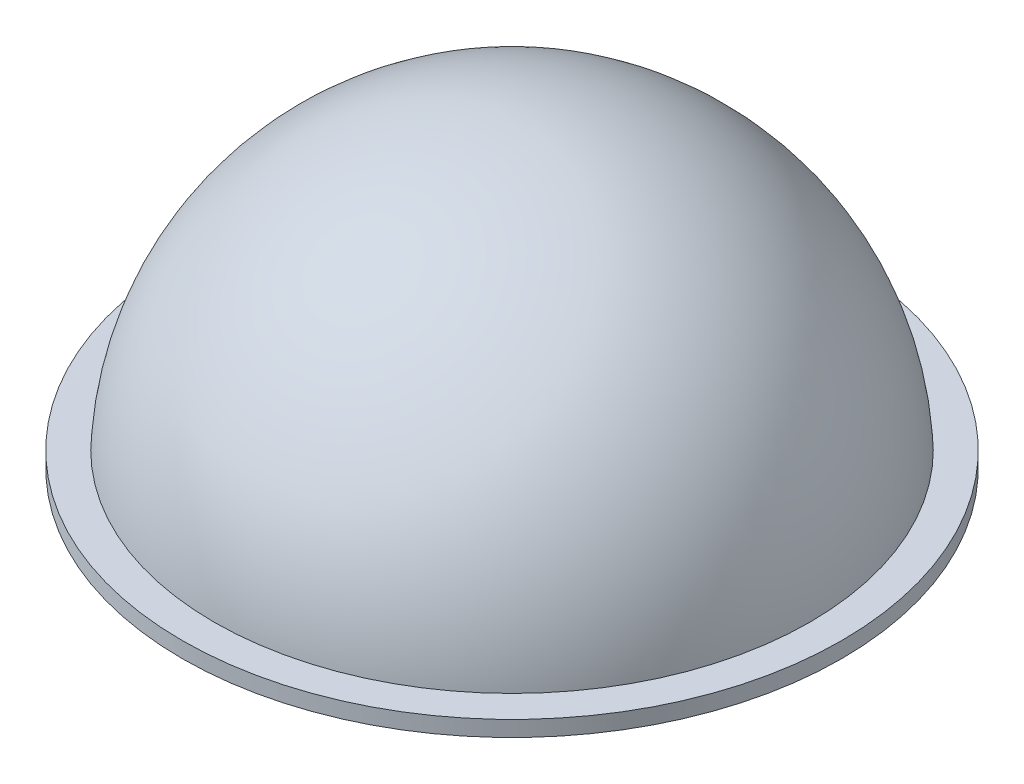
SolidWorks part; units mm, degrees
ref_plane "Front" through (0, 0, 0) normal (0, 0, 1) x (1, 0, 0)
ref_plane "Top" through (0, 0, 0) normal (0, 1, 0) x (1, 0, 0)
ref_plane "Right" through (0, 0, 0) normal (1, 0, 0) x (0, 0, -1)
sketch "Sketch1" plane through (0, 0, 0) normal (0, 0, 1) x (1, 0, 0)
  line L2 (-105, 0) -> (-105, 5)
  line L3 (-105, 5) -> (-94.8683, 5)
  line L8 (0, 0) -> (0, 95) construction
  line L9 (0, 95) -> (0, 90)
  line L10 (-105, 0) -> (95, 0) construction
  line L11 (-105, 0) -> (-90, 0)
  arc A0 (95, 0) -> (-95, 0) centre (0, 0) ccw construction
  arc A1 (0, 90) -> (-90, 0) centre (0, 0) ccw
  arc A2 (-94.8683, 5) -> (0, 95) centre (0, 0) cw
  dimension "D1" = 190
  dimension "D2" = 180
  dimension "D3" = 10
  dimension "D6" = 5
revolve "Revolve1" add sketch "Sketch1" angle 360 about L8
